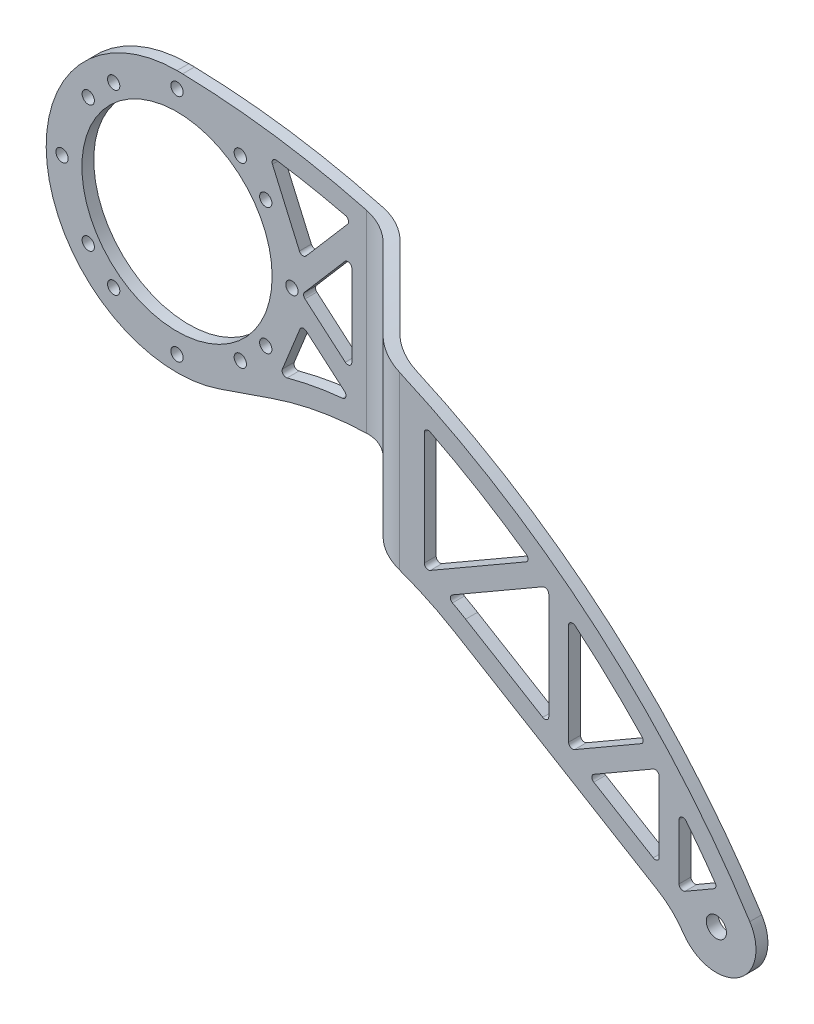
SolidWorks part; units mm, degrees
material "6061 合金"
ref_plane "前视基准面" through (0, 0, 0) normal (0, 0, 1) x (1, 0, 0)
ref_plane "上视基准面" through (0, 0, 0) normal (0, 1, 0) x (1, 0, 0)
ref_plane "右视基准面" through (0, 0, 0) normal (1, 0, 0) x (0, 0, -1)
other "Configuration Table"
sketch "草图1" plane through (0, 0, 0) normal (0, 0, 1) x (1, 0, 0)
  line L0 (-38.6665, 0) -> (31.2744, 0) construction
  line L1 (0, 22.4607) -> (0, -30.1372) construction
  line L4 (10.7304, -31.2067) -> (23.987, -26.6485)
  line L5 (91.2325, -33.7454) -> (142.3676, -64.5004)
  line L6 (157.0595, -65.0562) -> (0, 0) construction
  circle A7 centre (157.0595, -65.0562) radius 2.55
  arc A9 (0, 33) -> (10.7304, -31.2067) centre (0, 0) ccw
  arc A10 (148.7262, -70.5839) -> (165.4995, -59.6928) centre (157.0595, -65.0562) ccw
  arc A11 (1.4146, 32.9833) -> (165.4995, -59.6928) centre (-3.3007, -166.9611) cw
  arc A12 (23.987, -26.6485) -> (91.2325, -33.7454) centre (50, -102.3011) cw
  arc A13 (142.3676, -64.5004) -> (148.7262, -70.5839) centre (132.0595, -81.6393) cw
  arc A14 (1.4146, 32.9833) -> (0, 33) centre (0, -27) ccw
  dimension "D1" = 60
  dimension "D2" = 5.1
  dimension "D3" = 22.5
  dimension "D4" = 33
  dimension "D6" = 80
  dimension "D7" = 20
  dimension "D8" = 10
  dimension "D10" = 200
  dimension "D11" = 50
  dimension "D5" = 130
  dimension "D9" = 170
  dimension "D12" = 25
extrude "凸台-拉伸1" add sketch "草图1" along normal blind 3 and the other way blind 21
sketch "草图6" plane through (0, 0, 0) normal (0, 1, 0) x (1, 0, 0)
  line L0 (-33, 0) -> (47.8579, 0)
  line L2 (54.9289, 2.9289) -> (73, 21)
  line L3 (10.7304, 21) -> (-33, 21) construction
  line L5 (53.2426, -3) -> (71.3137, 15.0711)
  line L7 (78.3848, 18) -> (167.0595, 18)
  line L8 (167.0595, 18) -> (167.0595, -3)
  line L9 (167.0595, -3) -> (53.2426, -3)
  line L10 (73, 21) -> (-33, 21)
  line L12 (-33, 21) -> (-33, 0)
  line L13 (-33, 21) -> (-33, -3) construction
  line L14 (167.0595, -3) -> (167.0595, 21) construction
  line L15 (165.4995, 21) -> (1.4146, 21) construction
  line L16 (1.4146, -3) -> (165.4995, -3) construction
  arc A0 (71.3137, 15.0711) -> (78.3848, 18) centre (78.3848, 8) cw
  arc A1 (47.8579, 0) -> (54.9289, 2.9289) centre (47.8579, 10) ccw
  point P25 (52, 0)
  dimension "D5" = 10
  dimension "D1" = 3
  dimension "D2" = 3
  dimension "D3" = 45
  dimension "D4" = 85
extrude "切除-拉伸3" cut sketch "草图6" against normal through all both and the other way through all
sketch "草图2" plane through (0, 0, 3) normal (0, 0, 1) x (1, 0, 0)
  circle A0 centre (-29, 0) radius 1.55
  circle A2 centre (0, 0) radius 29 construction
  circle A3 centre (0, -29) radius 1.55
  circle A4 centre (0, 29) radius 1.55
  circle A5 centre (29, 0) radius 1.55
  dimension "D2" = 3.1
  dimension "D1" = 29
extrude "切除-拉伸1" cut sketch "草图2" against normal through all
sketch "草图4" plane through (0, 0, 3) normal (0, 0, 1) x (1, 0, 0)
  line L0 (35.2189, 0) -> (0, 0) construction
  line L1 (0, 0) -> (0, 39.685) construction
  line L2 (22.3882, 15.9693) -> (0, 0) construction
  line L3 (0, 0) -> (15.9693, 22.3882) construction
  line L4 (15.9693, -22.3882) -> (0, 0) construction
  line L5 (0, 0) -> (22.3882, -15.9693) construction
  line L6 (-22.3882, -15.9693) -> (0, 0) construction
  line L7 (0, 0) -> (-15.9693, -22.3882) construction
  line L8 (-15.9693, 22.3882) -> (0, 0) construction
  line L9 (0, 0) -> (-22.3882, 15.9693) construction
  circle A0 centre (0, 0) radius 27.5 construction
  circle A1 centre (-22.3882, 15.9693) radius 1.55
  circle A2 centre (15.9693, 22.3882) radius 1.55
  circle A3 centre (-15.9693, -22.3882) radius 1.55
  circle A4 centre (22.3882, -15.9693) radius 1.55
  circle A5 centre (-15.9693, 22.3882) radius 1.55
  circle A6 centre (22.3882, 15.9693) radius 1.55
  circle A7 centre (15.9693, -22.3882) radius 1.55
  circle A8 centre (-22.3882, -15.9693) radius 1.55
  point P16 (0, 0)
  dimension "D1" = 55
  dimension "D5" = 3.1
  dimension "D2" = 35.5
  dimension "D3" = 19
  dimension "D4" = 4
extrude "切除-拉伸2" cut sketch "草图4" against normal through all
fillet "圆角2" radius 10 2 edges at (73, -3.8831, -21) (53.2426, 1.2564, 3)
sketch "草图10" plane through (0, 0, 3) normal (0, 0, 1) x (1, 0, 0)
  circle A0 centre (0, 0) radius 24
  dimension "D1" = 48
extrude "切除-拉伸5" cut sketch "草图10" against normal through all
sketch "草图12" plane through (0, 0, -18) normal (0, 0, 1) x (1, 0, 0)
  line L0 (83.3848, 6.0917) -> (83.3848, -22.3996)
  line L1 (84.8848, -23.2657) -> (109.0475, -9.3153)
  line L4 (93.8095, -29.4607) -> (144.9447, -60.2157)
  line L5 (83.3848, 7.7118) -> (83.3848, -24.1317)
  line L11 (113.2813, -12.6445) -> (90.4641, -25.818)
  line L12 (93.8095, -29.4607) -> (113.2659, -41.1626)
  line L13 (114.7813, -13.5105) -> (114.7813, -40.3057)
  line L14 (119.7813, -17.8314) -> (119.7813, -43.3492)
  line L15 (121.2813, -44.2152) -> (138.1188, -34.4941)
  line L16 (126.1486, -47.1786) -> (141.1555, -38.5143)
  line L17 (142.6555, -39.3804) -> (142.6555, -57.0705)
  line L18 (147.6555, -46.3571) -> (147.6555, -60.3684)
  line L19 (126.1332, -48.9016) -> (141.1401, -57.9274)
  line L20 (156.4448, -57.026) -> (149.1555, -61.2345)
  arc A0 (109.124, -7.6322) -> (84.8368, 6.9837) centre (-3.3007, -166.9611) ccw
  arc A1 (138.3452, -32.9408) -> (121.4209, -17.0627) centre (-3.3007, -166.9611) ccw
  arc A2 (161.2795, -62.3745) -> (83.3848, 7.7118) centre (-3.3007, -166.9611) ccw
  arc A4 (156.7656, -55.5888) -> (149.4388, -45.7354) centre (-3.3007, -166.9611) ccw
  arc A5 (149.4263, -63.6561) -> (144.9447, -60.2157) centre (132.0595, -81.6393) ccw construction
  arc A22 (152.8929, -67.82) -> (144.9447, -60.2157) centre (132.0595, -81.6393) ccw
  arc A24 (152.8929, -67.82) -> (161.2795, -62.3745) centre (157.0595, -65.0562) ccw
  arc A25 (147.6555, -46.3571) -> (149.4388, -45.7354) centre (148.6555, -46.3571) cw
  arc A26 (126.1486, -47.1786) -> (126.1332, -48.9016) centre (126.6486, -48.0446) ccw
  arc A27 (141.1555, -38.5143) -> (142.6555, -39.3804) centre (141.6555, -39.3804) cw
  arc A28 (138.1188, -34.4941) -> (138.3452, -32.9408) centre (137.6188, -33.628) ccw
  arc A29 (119.7813, -43.3492) -> (121.2813, -44.2152) centre (120.7813, -43.3492) ccw
  arc A30 (119.7813, -17.8314) -> (121.4209, -17.0627) centre (120.7813, -17.8314) cw
  arc A31 (114.7813, -40.3057) -> (113.2659, -41.1626) centre (113.7813, -40.3057) cw
  arc A32 (90.4641, -25.818) -> (90.4877, -27.5633) centre (90.9641, -26.684) ccw
  arc A33 (113.2813, -12.6445) -> (114.7813, -13.5105) centre (113.7813, -13.5105) cw
  arc A34 (109.0475, -9.3153) -> (109.124, -7.6322) centre (108.5475, -8.4493) ccw
  arc A35 (84.8848, -23.2657) -> (83.3848, -22.3996) centre (84.3848, -22.3996) cw
  arc A36 (84.8368, 6.9837) -> (83.3848, 6.0917) centre (84.3848, 6.0917) ccw
  arc A37 (142.6555, -57.0705) -> (141.1401, -57.9274) centre (141.6555, -57.0705) cw
  arc A38 (147.6555, -60.3684) -> (149.1555, -61.2345) centre (148.6555, -60.3684) ccw
  arc A39 (156.7656, -55.5888) -> (156.4448, -57.026) centre (155.9448, -56.16) cw
  arc A41 (93.8095, -29.4607) -> (83.3848, -24.1317) centre (50, -102.3011) ccw
  arc A42 (93.8095, -29.4607) -> (90.4877, -27.5633) centre (50, -102.3011) ccw
  point P5 (147.6555, -62.1005)
  point P19 (83.3848, -24.1317)
  point P30 (147.6555, -62.1005)
  point P35 (124.6791, -48.027)
  point P38 (142.6555, -37.6483)
  point P41 (139.212, -33.8629)
  point P44 (399.0304, 162.0422)
  point P45 (119.7813, -45.0813)
  point P54 (114.7813, -11.7784)
  point P57 (110.3955, -8.537)
  dimension "D6" = 60
  dimension "D9" = 5
  dimension "D2" = 5
  dimension "D11" = 60
  dimension "D12" = 1
  dimension "D13" = 1
  dimension "D7" = 1
  dimension "D3" = 5
  dimension "D4" = 60
  dimension "D5" = 60
  dimension "D8" = 5
  dimension "D1" = 5
extrude "切除-拉伸6" cut sketch "草图12" against normal through all
sketch "草图13" plane through (0, 0, 3) normal (0, 0, 1) x (1, 0, 0)
  line L0 (32.9388, 0) -> (0, 0) construction
  line L2 (24.0827, 24.5625) -> (30.8907, 9.0204)
  line L3 (32.565, 8.7697) -> (43.0399, 20.9561)
  line L4 (44.1005, -17.5061) -> (44.1005, 22.19)
  line L5 (9.1045, -26.4784) -> (22.3612, -21.9202)
  line L6 (44.1005, -8.7346) -> (44.1005, 11.822)
  line L8 (32.1804, 0.6518) -> (42.3422, 12.4738)
  line L9 (32.2869, -0.7584) -> (42.4487, -9.493)
  line L10 (32.5853, -7.6081) -> (42.2904, -15.9502)
  line L11 (31.0063, -7.9916) -> (26.5896, -18.9173)
  circle A0 centre (22.3882, -15.9693) radius 1.55 construction
  arc A1 (41.7358, -17.7038) -> (42.2904, -15.9502) centre (41.6386, -16.7085) ccw
  arc A2 (26.5896, -18.9173) -> (27.7781, -20.2573) centre (27.5167, -19.2921) ccw
  arc A3 (32.1804, 0.6518) -> (32.2869, -0.7584) centre (32.9388, 0) ccw
  arc A4 (32.5853, -7.6081) -> (31.0063, -7.9916) centre (31.9335, -8.3664) ccw
  arc A5 (42.4487, -9.493) -> (44.1005, -8.7346) centre (43.1005, -8.7346) ccw
  arc A6 (42.3422, 12.4738) -> (44.1005, 11.822) centre (43.1005, 11.822) cw
  arc A7 (30.8907, 9.0204) -> (32.565, 8.7697) centre (31.8066, 9.4216) ccw
  arc A8 (43.0399, 20.9561) -> (42.5165, 22.5799) centre (42.2815, 21.6079) ccw
  arc A9 (24.0827, 24.5625) -> (25.1446, 25.9531) centre (24.9987, 24.9638) cw
  circle A10 centre (22.3882, 15.9693) radius 1.55 construction
  arc A18 (44.1005, -17.5061) -> (22.3612, -21.9202) centre (50, -102.3011) ccw
  arc A19 (44.1005, 22.19) -> (1.2967, 27.9847) centre (-3.3007, -166.9611) ccw
  arc A20 (1.2967, 27.9847) -> (0, 28) centre (0, -27) ccw
  arc A21 (0, 28) -> (9.1045, -26.4784) centre (0, 0) ccw
  arc A22 (41.7358, -17.7038) -> (27.7781, -20.2573) centre (50, -102.3011) ccw
  arc A23 (42.5165, 22.5799) -> (25.1446, 25.9531) centre (-3.3007, -166.9611) ccw
  point P24 (31.5286, -0.1065)
  point P27 (31.5286, -6.6998)
  point P30 (44.1005, -10.9128)
  point P33 (44.1005, 14.5195)
  point P36 (31.5286, 7.564)
  dimension "D6" = 5
  dimension "D7" = 1
  dimension "D2" = 5
  dimension "D3" = 5
  dimension "D4" = 5
  dimension "D1" = 5
extrude "切除-拉伸7" cut sketch "草图13" against normal through all
mirror "镜向1" about plane through (132.0595, -81.6393, 3) normal (0, 0, -1) of bodies 115
delete or keep bodies "实体-删除/保留 1" type delete bodies bodies 115
